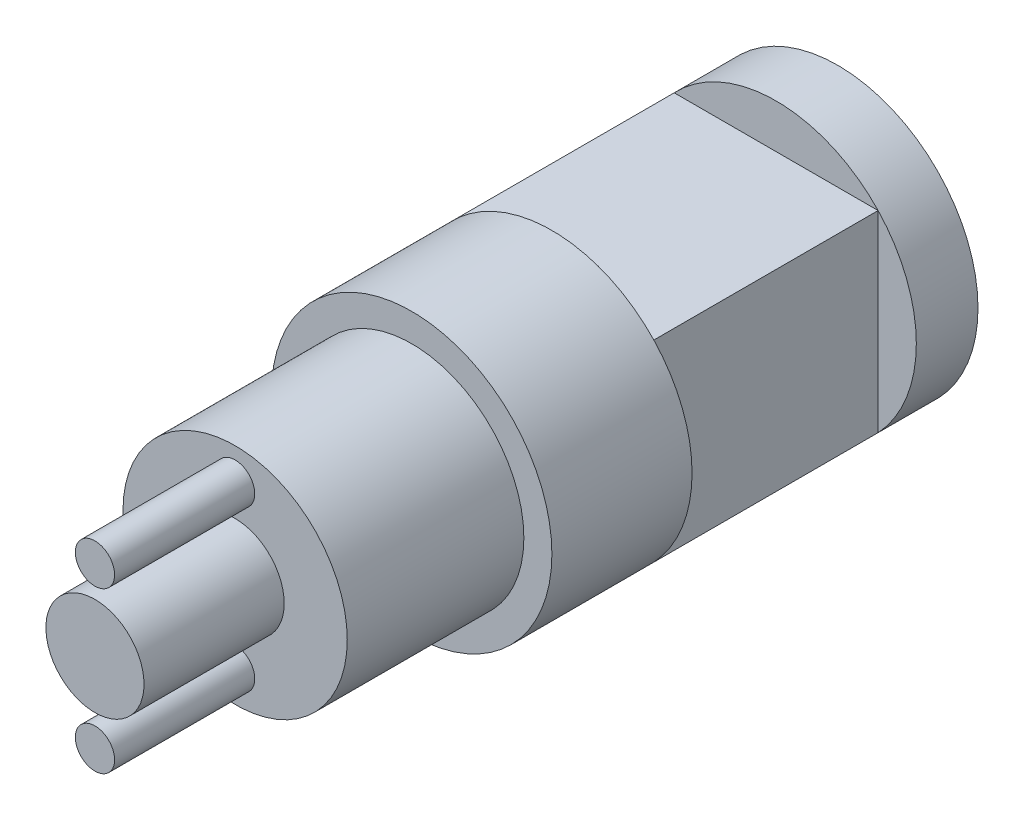
SolidWorks part; units mm, degrees
ref_plane "Front Plane" through (0, 0, 0) normal (0, 0, 1) x (1, 0, 0)
ref_plane "Top Plane" through (0, 0, 0) normal (0, 1, 0) x (1, 0, 0)
ref_plane "Right Plane" through (0, 0, 0) normal (1, 0, 0) x (0, 0, -1)
sketch "Cylinder Face" plane through (0, 0, 0) normal (0, 0, 1) x (1, 0, 0)
  circle A0 centre (0, 0) radius 5
  dimension "D1" = 10
extrude "Base Cylinder" add sketch "Cylinder Face" along normal blind 2.2
sketch "rectangular thing" plane through (0, 0, 2.2) normal (0, 0, 1) x (1, 0, 0)
  line L1 (3.6371, 3.431) -> (-3.6371, 3.431)
  line L2 (3.6371, 3.431) -> (3.6371, -3.431)
  line L3 (3.6371, -3.431) -> (-3.6371, -3.431)
  line L4 (-3.6371, 3.431) -> (-3.6371, -3.431)
  line L5 (3.6371, 3.431) -> (-3.6371, -3.431) construction
  line L6 (3.6371, -3.431) -> (-3.6371, 3.431) construction
  circle A0 centre (0, 0) radius 5 construction
  point P0 (0, 0)
  point P6 (3.3707, 3.5245)
  point P7 (0, 0)
  point P8 (3.345, 3.8064)
  point P9 (3.5373, 3.5338)
  point P12 (-3.6829, 3.3817)
  point P13 (0, 0)
  point P14 (-3.7007, 3.3623)
  point P15 (-3.6561, 3.4107)
  point P16 (0, 0)
  point P17 (0, 0)
  point P18 (0, 0)
  point P19 (0, 0)
  point P20 (-3.6371, 3.431)
extrude "rectangular" add sketch "rectangular thing" along normal blind 8
sketch "Sketch5" plane through (0, 0, 10.2) normal (0, 0, 1) x (1, 0, 0)
  circle A0 centre (0, 0) radius 5
extrude "2nd Cylinder" add sketch "Sketch5" along normal blind 5
sketch "Sketch6" plane through (0, 0, 15.2) normal (0, 0, 1) x (1, 0, 0)
  circle A0 centre (0, 0) radius 4
  dimension "D1" = 8
extrude "3rd Cylinder" add sketch "Sketch6" along normal blind 6.3 contours A0
sketch "Sketch7" plane through (0, 0, 21.5) normal (0, 0, 1) x (1, 0, 0)
  circle A0 centre (0, 0) radius 1.75
  dimension "D1" = 3.5
extrude "Top Cylinder" add sketch "Sketch7" along normal blind 5
sketch "Sketch9" plane through (0, 0, 21.5) normal (0, 0, 1) x (1, 0, 0)
  line L0 (0, -5.1145) -> (0, 5.2069) construction
  line L1 (-5.8338, 0) -> (6.0054, 0) construction
  circle A0 centre (0, 2.8575) radius 0.7
  circle A1 centre (0, -2.8575) radius 0.7
  dimension "D1" = 1.4
extrude "Prongs?" add sketch "Sketch9" along normal blind 5
sketch "Sketch10" plane through (0, 0, 0) normal (0, 0, -1) x (-1, 0, 0)
  text T0 "LED"
  point P1 (-3.7352, -1.2209)
  point P2 (-3.9728, -1.5772)
  point P3 (0, 0)
  point P4 (-4.2104, -1.7224)
  point P5 (0, 0)
  point P6 (-3.9068, -1.5376)
  point P7 (0, 0)
  point P8 (0, 0)
extrude "Cut-Extrude1" cut sketch "Sketch10" against normal blind 1
